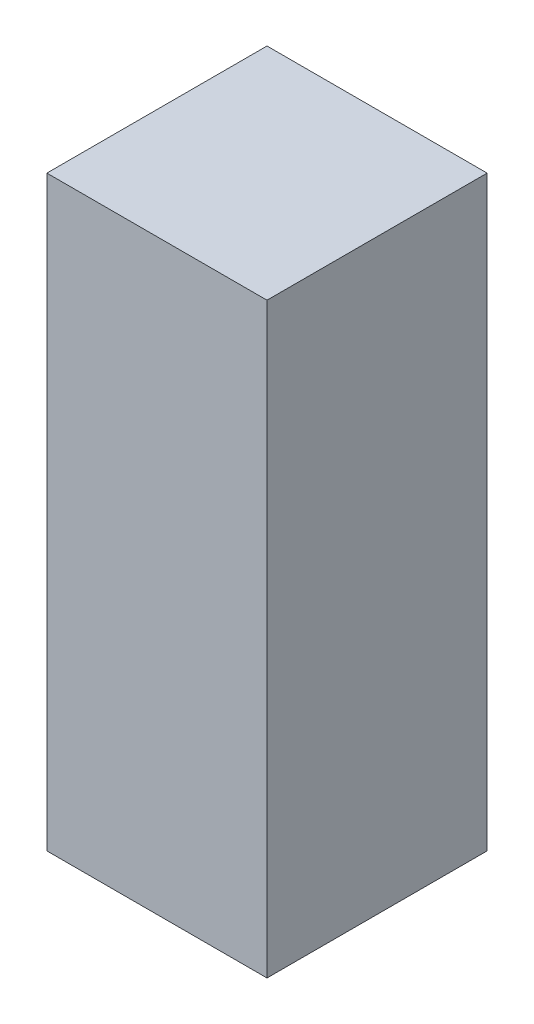
SolidWorks part; units mm, degrees
ref_plane "Front Plane" through (0, 0, 0) normal (0, 0, 1) x (1, 0, 0)
ref_plane "Top Plane" through (0, 0, 0) normal (0, 1, 0) x (1, 0, 0)
ref_plane "Right Plane" through (0, 0, 0) normal (1, 0, 0) x (0, 0, -1)
sketch "Sketch1" plane through (0, 0, 0) normal (0, 1, 0) x (1, 0, 0)
  line L1 (0, 0) -> (1.5, 0)
  line L2 (0, 0) -> (0, 1.5)
  line L3 (0, 1.5) -> (1.5, 1.5)
  line L4 (1.5, 0) -> (1.5, 1.5)
  dimension "D1" = 1.5
  dimension "D2" = 1.5
extrude "Boss-Extrude1" add sketch "Sketch1" along normal blind 4
